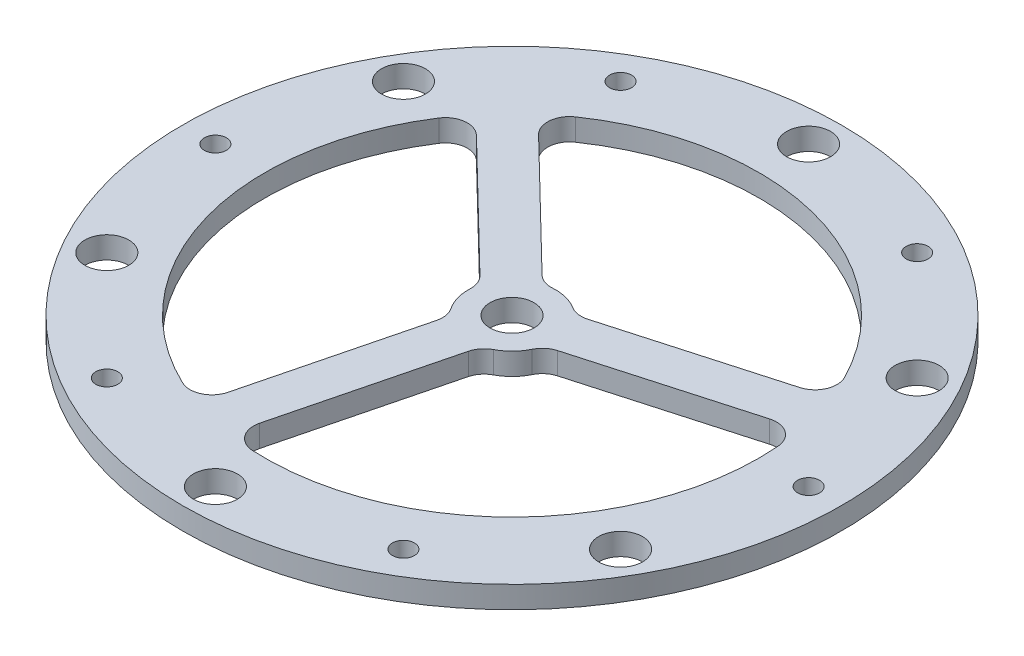
SolidWorks part; units mm, degrees
ref_plane "Front Plane" through (0, 0, 0) normal (0, 0, 1) x (1, 0, 0)
ref_plane "Top Plane" through (0, 0, 0) normal (0, 1, 0) x (1, 0, 0)
ref_plane "Right Plane" through (0, 0, 0) normal (1, 0, 0) x (0, 0, -1)
sketch "Sketch1" plane through (0, 0, 0) normal (0, 1, 0) x (1, 0, 0)
  circle A0 centre (0, 0) radius 30
  circle A1 centre (0, 0) radius 27 construction
  circle A2 centre (0, 27) radius 2
  circle A3 centre (23.3827, 13.5) radius 2
  circle A4 centre (23.3827, -13.5) radius 2
  circle A5 centre (0, -27) radius 2
  circle A6 centre (-23.3827, -13.5) radius 2
  circle A7 centre (-23.3827, 13.5) radius 2
  point P18 (0, 0)
  dimension "D1" = 60
  dimension "D2" = 54
  dimension "D3" = 4
  dimension "D4" = 6
extrude "Boss-Extrude1" add sketch "Sketch1" along normal blind 2
sketch "Sketch3" plane through (0, 2, 0) normal (0, 1, 0) x (1, 0, 0)
  line L0 (-13.5, 23.3827) -> (0, 0) construction
  line L1 (0, 0) -> (12.944, 0) construction
  circle A0 centre (0, 0) radius 27 construction
  circle A1 centre (-13.5, 23.3827) radius 1
  circle A2 centre (13.5, 23.3827) radius 1
  circle A3 centre (27, 0) radius 1
  circle A4 centre (13.5, -23.3827) radius 1
  circle A5 centre (-13.5, -23.3827) radius 1
  circle A6 centre (-27, 0) radius 1
  point P17 (0, 0)
  dimension "D1" = 54
  dimension "D2" = 2
  dimension "D4" = 120
  dimension "D3" = 6
extrude "Cut-Extrude1" cut sketch "Sketch3" against normal blind 3
sketch "Sketch4" plane through (0, 2, 0) normal (0, 1, 0) x (1, 0, 0)
  line L0 (-1.0909, 3.8484) -> (-14.6801, 17.0512)
  line L1 (21.016, 8.0361) -> (2.7873, 2.8689)
  line L2 (-30.5857, 29.716) -> (0, 0) construction
  line L5 (0, 0) -> (36.11, 10.236) construction
  arc A3 (-14.6801, 17.0512) -> (21.016, 8.0361) centre (0, 0) cw
  arc A4 (2.7873, 2.8689) -> (-1.0909, 3.8484) centre (0, 0) ccw
  circle A5 centre (0, 0) radius 2
  dimension "D3" = 4
  dimension "D4" = 4
  dimension "D5" = 4
  dimension "D2" = 4
  dimension "D6" = 22.5
  dimension "D1" = 120
extrude "Cut-Extrude2" cut sketch "Sketch4" against normal blind 10
fillet "Fillet1" radius 2 4 edges at (21.016, 1, -8.0361) (2.7873, 1, -2.8689) (-1.0909, 1, -3.8484) (-14.6801, 1, -17.0512)
pattern_circular "CirPattern1" count 3 over 360 about axis through (0, 0, 0) along (0, 1, 0) of "Cut-Extrude2", "Fillet1"
